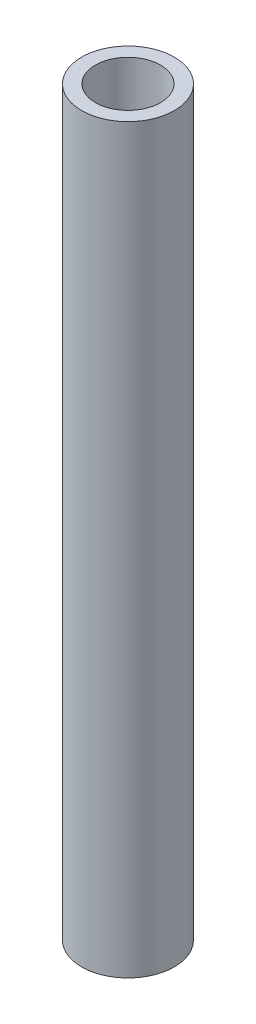
SolidWorks part; units mm, degrees
ref_plane "Front Plane" through (0, 0, 0) normal (0, 0, 1) x (1, 0, 0)
ref_plane "Top Plane" through (0, 0, 0) normal (0, 1, 0) x (1, 0, 0)
ref_plane "Right Plane" through (0, 0, 0) normal (1, 0, 0) x (0, 0, -1)
sketch "Sketch1" plane through (0, 0, 0) normal (0, 1, 0) x (1, 0, 0)
  circle A0 centre (0, 0) radius 6.5
  circle A1 centre (0, 0) radius 9.25
  point P5 (0.6974, 0)
  dimension "D1" = 18.5
  dimension "D2" = 13
extrude "Boss-Extrude1" add sketch "Sketch1" along normal blind 148
